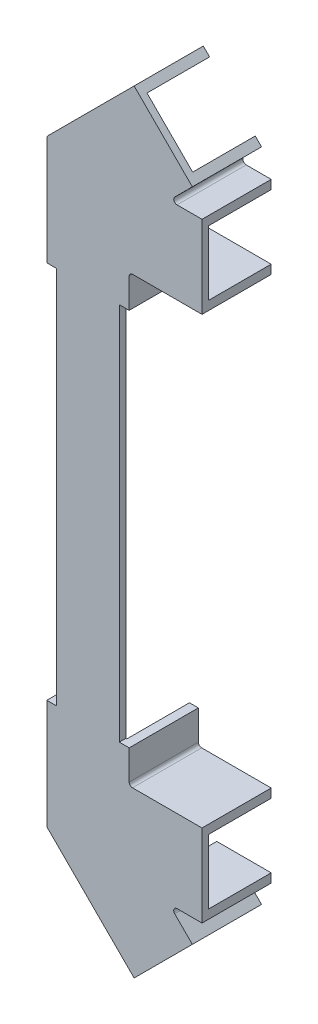
SolidWorks part; units mm, degrees
ref_plane "Front Plane" through (0, 0, 0) normal (0, 0, 1) x (1, 0, 0)
ref_plane "Top Plane" through (0, 0, 0) normal (0, 1, 0) x (1, 0, 0)
ref_plane "Right Plane" through (0, 0, 0) normal (1, 0, 0) x (0, 0, -1)
sketch "Sketch1" plane through (0, 0, 0) normal (0, 0, 1) x (1, 0, 0)
  line L0 (-9.5, -67.5) -> (-12.5, -67.5)
  line L1 (-12.5, -67.5) -> (-12.5, -90.7417)
  line L2 (-12.5, -90.7417) -> (14.007, -117.2487)
  line L3 (14.007, -117.2487) -> (31.6847, -99.5711)
  line L4 (31.6847, -99.5711) -> (24.6136, -92.5)
  line L5 (24.6136, -92.5) -> (34.6136, -92.5)
  line L6 (34.6136, -92.5) -> (34.6136, -67.5)
  line L7 (34.6136, -67.5) -> (9.5, -67.5)
  line L8 (9.5, -70.5) -> (9.5, 70.5) construction
  line L9 (9.5, -67.5) -> (9.5, 67.5)
  line L10 (9.5, 67.5) -> (34.6136, 67.5)
  line L11 (34.6136, 67.5) -> (34.6136, 92.5)
  line L12 (34.6136, 92.5) -> (24.6136, 92.5)
  line L13 (24.6136, 92.5) -> (31.6847, 99.5711)
  line L14 (31.6847, 99.5711) -> (14.007, 117.2487)
  line L15 (14.007, 117.2487) -> (-12.5, 90.7417)
  line L16 (-12.5, 90.7417) -> (-12.5, 67.5)
  line L17 (-12.5, 67.5) -> (-9.5, 67.5)
  line L18 (-9.5, 67.5) -> (-9.5, -67.5)
  line L19 (151, -249.9991) -> (-9.4991, -89.5) construction
  line L20 (151, -223.129) -> (17.371, -89.5) construction
  line L21 (-9.4991, 89.5) -> (151, 249.9991) construction
  line L22 (490.5, -89.5) -> (-9.5, -89.5) construction
  line L23 (490.5, -70.5) -> (-9.5, -70.5) construction
  line L24 (-9.5, -70.5) -> (-9.5, -89.5) construction
  line L25 (-9.5, 70.5) -> (490.5, 70.5) construction
  line L26 (-9.5, 80) -> (-9.5, -80) construction
  dimension "D1" = 3
  dimension "D2" = 3
  dimension "D3" = 3
  dimension "D4" = 3
  dimension "D5" = 3
  dimension "D6" = 10
  dimension "D7" = 10
  dimension "D8" = 3
extrude "Boss-Extrude1" add sketch "Sketch1" along normal blind 2
sketch "Sketch2" plane through (0, 0, 0) normal (0, 0, -1) x (-1, 0, 0)
  line L0 (-34.6136, 89.8) -> (-34.6136, 92.5)
  line L1 (-34.6136, 67.5) -> (-34.6136, 92.5) construction
  line L2 (-34.6136, 92.5) -> (-24.6136, 92.5)
  line L3 (-24.6136, 92.5) -> (-31.6847, 99.5711)
  line L4 (-31.6847, 99.5711) -> (-29.7755, 101.4803)
  line L5 (-31.6847, 99.5711) -> (-14.007, 117.2487) construction
  line L6 (-29.7755, 101.4803) -> (-18.0952, 89.8)
  line L7 (-18.0952, 89.8) -> (-34.6136, 89.8)
  line L8 (9.5, 89.5) -> (-490.5, 89.5) construction
  line L9 (-9.5, -67.5) -> (-9.5, 67.5) construction
  line L10 (-34.6136, 67.5) -> (-9.8, 67.5)
  line L11 (-34.6136, 67.5) -> (-34.6136, 70.2)
  line L12 (-34.6136, 70.2) -> (-9.8, 70.2)
  line L13 (-9.8, 67.5) -> (-9.8, 70.2)
  line L14 (9.5, 70.5) -> (-490.5, 70.5) construction
  line L15 (9.8, 67.5) -> (12.5, 67.5)
  line L16 (12.5, 67.5) -> (9.5, 67.5) construction
  line L17 (12.5, 67.5) -> (12.5, 90.7417)
  line L18 (12.5, 90.7417) -> (12.5, 67.5) construction
  line L19 (12.5, 90.7417) -> (-14.007, 117.2487)
  line L20 (-14.007, 117.2487) -> (-15.9162, 115.3395)
  line L21 (-15.9162, 115.3395) -> (9.8, 89.6234)
  line L22 (9.8, 89.6234) -> (9.8, 67.5)
  line L23 (9.5, 67.5) -> (9.5, -67.5) construction
  line L24 (9.4991, 89.5) -> (-151, 249.9991) construction
  line L25 (-14.007, 117.2487) -> (12.5, 90.7417) construction
  line L26 (-31.6847, -99.5711) -> (-29.7755, -101.4803)
  line L27 (-14.007, -117.2487) -> (-31.6847, -99.5711) construction
  line L28 (-29.7755, -101.4803) -> (-18.0952, -89.8)
  line L29 (-18.0952, -89.8) -> (-34.6136, -89.8)
  line L30 (-34.6136, -92.5) -> (-34.6136, -67.5) construction
  line L31 (-34.6136, -89.8) -> (-34.6136, -92.5)
  line L32 (-34.6136, -92.5) -> (-24.6136, -92.5)
  line L33 (-24.6136, -92.5) -> (-31.6847, -99.5711)
  line L34 (-31.6847, -99.5711) -> (-24.6136, -92.5) construction
  line L35 (-34.6136, -67.5) -> (-9.5, -67.5) construction
  line L36 (-34.6136, -67.5) -> (-9.8, -67.5)
  line L37 (-34.6136, -67.5) -> (-34.6136, -70.2)
  line L38 (-34.6136, -70.2) -> (-9.8, -70.2)
  line L39 (-9.8, -67.5) -> (-9.8, -70.2)
  line L40 (-14.007, -117.2487) -> (-15.9162, -115.3395)
  line L41 (-15.9162, -115.3395) -> (9.8, -89.6234)
  line L42 (9.8, -89.6234) -> (9.8, -67.5)
  line L43 (9.5, -67.5) -> (12.5, -67.5) construction
  line L44 (9.8, -67.5) -> (12.5, -67.5)
  line L45 (12.5, -67.5) -> (12.5, -90.7417)
  line L46 (12.5, -90.7417) -> (-14.007, -117.2487)
  dimension "D1" = 0.3
  dimension "D2" = 0.3
  dimension "D3" = 0.3
  dimension "D4" = 0.3
  dimension "D5" = 0.3
extrude "Boss-Extrude2" add sketch "Sketch2" along normal blind 19
sketch "Sketch3" plane through (0, 0, 2) normal (0, 0, 1) x (1, 0, 0)
  line L0 (9.5, -67.5) -> (9.5, 67.5) construction
  line L1 (-12.5, -67.5) -> (12.5, -67.5)
  line L2 (-12.5, -67.5) -> (-12.5, -57.5)
  line L3 (-12.5, -57.5) -> (12.5, -57.5)
  line L4 (12.5, -67.5) -> (12.5, -57.5)
  line L5 (-12.5, 67.5) -> (12.5, 67.5)
  line L6 (-12.5, 67.5) -> (-12.5, 57.5)
  line L7 (-12.5, 57.5) -> (12.5, 57.5)
  line L8 (12.5, 67.5) -> (12.5, 57.5)
  dimension "D1" = 10
  dimension "D2" = 3
extrude "Boss-Extrude3" add sketch "Sketch3" against normal blind 2
sketch "Sketch4" plane through (0, 0, 0) normal (0, 0, -1) x (-1, 0, 0)
  line L1 (9.8, 67.5) -> (12.5, 67.5)
  line L2 (9.8, 67.5) -> (9.8, 57.5)
  line L3 (9.8, 57.5) -> (12.5, 57.5)
  line L4 (12.5, 67.5) -> (12.5, 57.5)
  line L5 (-9.8, 67.5) -> (-12.5, 67.5)
  line L6 (-9.8, 67.5) -> (-9.8, 57.5)
  line L7 (-9.8, 57.5) -> (-12.5, 57.5)
  line L8 (-12.5, 67.5) -> (-12.5, 57.5)
  line L9 (9.8, -67.5) -> (12.5, -67.5)
  line L10 (9.8, -67.5) -> (9.8, -57.5)
  line L11 (9.8, -57.5) -> (12.5, -57.5)
  line L12 (12.5, -67.5) -> (12.5, -57.5)
  line L13 (-9.8, -67.5) -> (-12.5, -67.5)
  line L14 (-9.8, -67.5) -> (-9.8, -57.5)
  line L15 (-9.8, -57.5) -> (-12.5, -57.5)
  line L16 (-12.5, -67.5) -> (-12.5, -57.5)
extrude "Boss-Extrude4" add sketch "Sketch4" along normal up to surface (19 mm away) up to face at (22.2068, -68.85, -19)
fillet "Fillet1" radius 1 6 edges at (-12.5, 90.7417, -8.5) (-12.5, -90.7417, -8.5) (24.6136, -92.5, -8.5) (24.6136, 92.5, -8.5) (12.5, 67.5, -8.5) (12.5, -67.5, -8.5)
equation "\"D2@Sketch2\"=\"D1@Sketch2\""
equation "\"D3@Sketch2\"=\"D1@Sketch2\""
equation "\"D4@Sketch2\"=\"D1@Sketch2\""
equation "\"D5@Sketch2\"=\"D1@Sketch2\""
